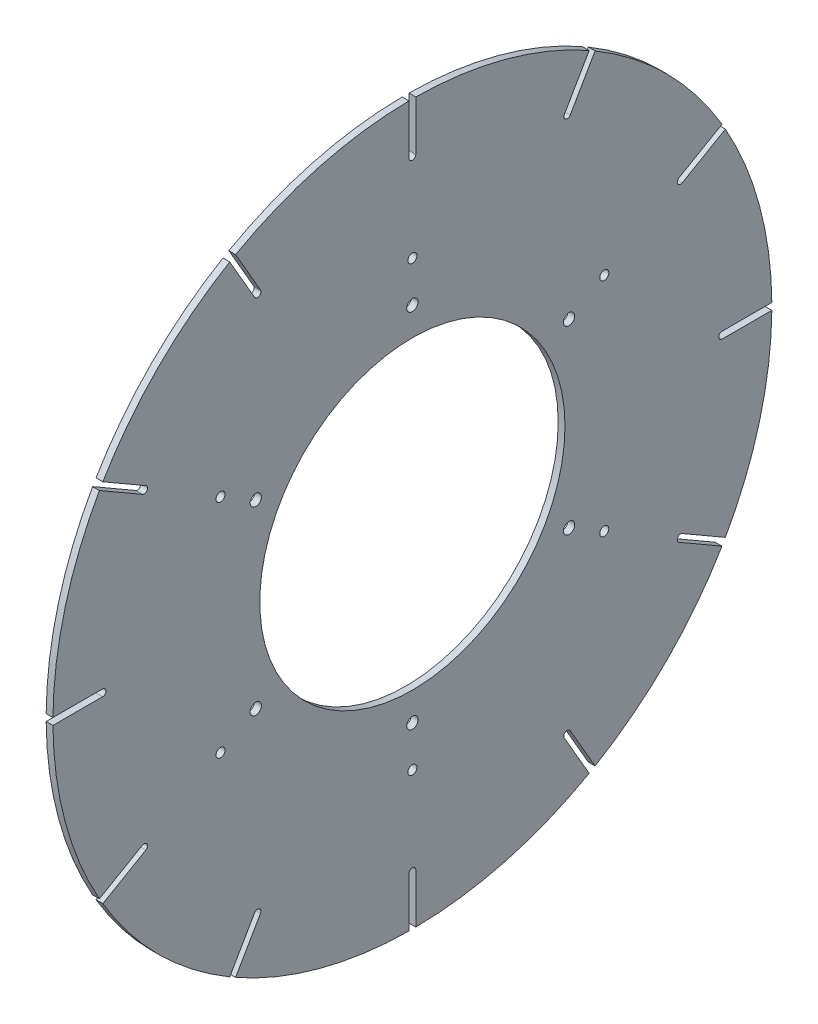
SolidWorks part; units mm, degrees
material "Alloy Steel"
ref_plane "Front Plane" through (0, 0, 0) normal (0, 0, 1) x (1, 0, 0)
ref_plane "Top Plane" through (0, 0, 0) normal (0, 1, 0) x (1, 0, 0)
ref_plane "Right Plane" through (0, 0, 0) normal (1, 0, 0) x (0, 0, -1)
sketch "Sketch1" plane through (0, 0, 0) normal (1, 0, 0) x (0, 0, -1)
  circle A0 centre (0, 0) radius 159
  dimension "D1" = 318
extrude "Boss-Extrude1" add sketch "Sketch1" along normal blind 3
sketch "Sketch2" plane through (3, 0, 0) normal (1, 0, 0) x (0, 0, -1)
  circle A0 centre (0, 0) radius 98 construction
  circle A1 centre (0, -98) radius 2
  circle A2 centre (-84.8705, -49) radius 2
  circle A3 centre (-84.8705, 49) radius 2
  circle A4 centre (0, 98) radius 2
  circle A5 centre (84.8705, 49) radius 2
  circle A6 centre (84.8705, -49) radius 2
  circle A7 centre (0, 0) radius 150 construction
  circle A8 centre (0, -150) radius 1.5
  circle A9 centre (-129.9038, -75) radius 1.5
  circle A10 centre (-129.9038, 75) radius 1.5
  circle A11 centre (0, 150) radius 1.5
  circle A12 centre (129.9038, 75) radius 1.5
  circle A13 centre (129.9038, -75) radius 1.5
  circle A14 centre (0, 0) radius 80 construction
  circle A15 centre (0, -80) radius 2.5
  circle A16 centre (-69.282, -40) radius 2.5
  circle A17 centre (-69.282, 40) radius 2.5
  circle A18 centre (0, 80) radius 2.5
  circle A19 centre (69.282, 40) radius 2.5
  circle A20 centre (69.282, -40) radius 2.5
  circle A21 centre (0, 0) radius 67.5
  point P18 (0, 0)
  point P32 (0, 0)
  point P46 (0, 0)
  dimension "D1" = 196
  dimension "D2" = 4
  dimension "D4" = 300
  dimension "D5" = 3
  dimension "D7" = 160
  dimension "D8" = 5
  dimension "D10" = 135
  dimension "D3" = 6
  dimension "D6" = 6
  dimension "D9" = 6
extrude "Cut-Extrude1" cut sketch "Sketch2" against normal blind 3
sketch "Sketch3" plane through (3, 0, 0) normal (1, 0, 0) x (0, 0, -1)
  line L0 (-1000, 0) -> (49000, 0) construction
  line L1 (-861.1036, -497.1584) -> (42194.077, 24360.7617) construction
  line L2 (118.6455, 68.5) -> (149.4596, 86.2905) construction
  line L3 (117.8955, 69.799) -> (148.7096, 87.5896)
  line L4 (119.3955, 67.201) -> (150.2096, 84.9915)
  circle A0 centre (0, 0) radius 137 construction
  arc A1 (117.8955, 69.799) -> (119.3955, 67.201) centre (118.6455, 68.5) ccw
  arc A2 (150.2096, 84.9915) -> (148.7096, 87.5896) centre (149.4596, 86.2905) ccw
  point P9 (134.0525, 77.3953)
  dimension "D1" = 274
  dimension "D2" = 30
  dimension "D3" = 3
extrude "Cut-Extrude2" cut sketch "Sketch3" against normal through all
pattern_circular "CirPattern1" count 12 over 360 about axis through (0, 0, 0) along (1, 0, 0) of "Cut-Extrude2"
